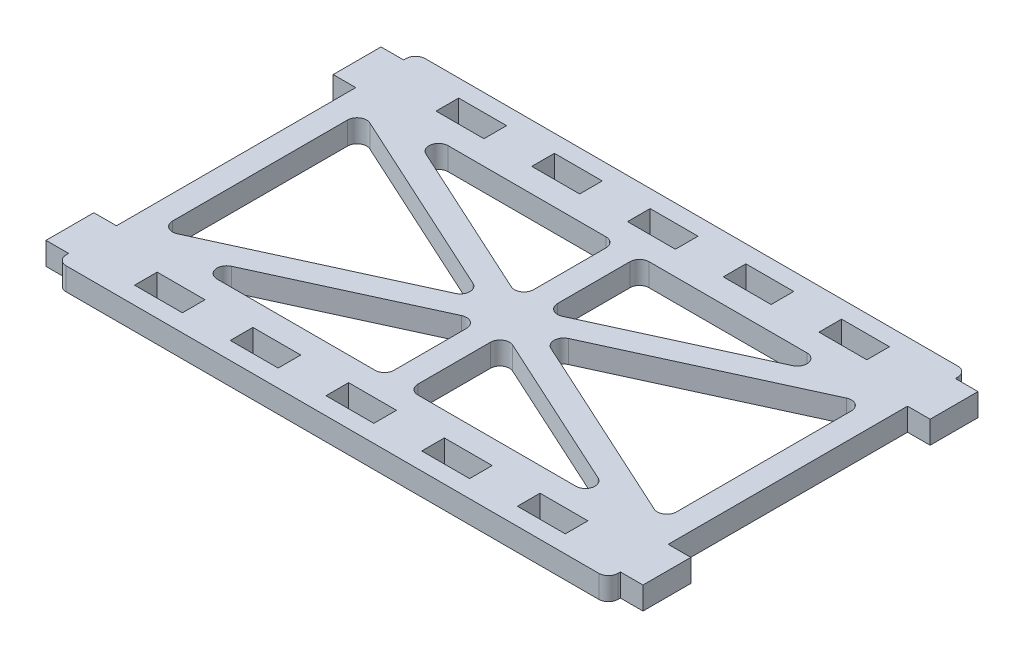
SolidWorks part; units mm, degrees
ref_plane "Front Plane" through (0, 0, 0) normal (0, 0, 1) x (1, 0, 0)
ref_plane "Top Plane" through (0, 0, 0) normal (0, 1, 0) x (1, 0, 0)
ref_plane "Right Plane" through (0, 0, 0) normal (1, 0, 0) x (0, 0, -1)
sketch "Sketch1" plane through (0, 0, 0) normal (0, 1, 0) x (1, 0, 0)
  line L1 (76.2, -50.8) -> (-76.2, -50.8) construction
  line L2 (76.2, -50.8) -> (76.2, 50.8) construction
  line L3 (76.2, 50.8) -> (-76.2, 50.8) construction
  line L4 (-76.2, -50.8) -> (-76.2, 50.8) construction
  line L5 (76.2, -50.8) -> (-76.2, 50.8) construction
  line L6 (76.2, 50.8) -> (-76.2, -50.8) construction
  line L7 (73.2, -47.625) -> (-73.2, -47.625)
  line L8 (73.2, -47.625) -> (73.2, 47.625)
  line L9 (73.2, 47.625) -> (-73.2, 47.625)
  line L10 (-73.2, -47.625) -> (-73.2, 47.625)
  line L11 (73.2, -47.625) -> (-73.2, 47.625) construction
  line L12 (73.2, 47.625) -> (-73.2, -47.625) construction
  line L13 (-73.2, -50.8) -> (-79.2, -50.8) construction
  line L14 (-73.2, -50.8) -> (-73.2, 50.8) construction
  line L15 (-73.2, 50.8) -> (-79.2, 50.8) construction
  line L16 (-79.2, -50.8) -> (-79.2, 50.8) construction
  line L17 (-73.2, -50.8) -> (-79.2, 50.8) construction
  line L18 (-73.2, 50.8) -> (-79.2, -50.8) construction
  line L19 (73.2, -50.8) -> (79.2, -50.8) construction
  line L20 (73.2, -50.8) -> (73.2, 50.8) construction
  line L21 (73.2, 50.8) -> (79.2, 50.8) construction
  line L22 (79.2, -50.8) -> (79.2, 50.8) construction
  line L23 (73.2, -50.8) -> (79.2, 50.8) construction
  line L24 (73.2, 50.8) -> (79.2, -50.8) construction
  point P0 (0, 0)
  point P6 (0, 0)
  point P11 (-76.2, 0)
  point P16 (76.2, 0)
  dimension "D1" = 152.4
  dimension "D2" = 101.6
  dimension "D4" = 6
  dimension "D5" = 95.25
extrude "Boss-Extrude1" add sketch "Sketch1" along normal mid plane 6
sketch "Sketch2" plane through (0, 3, 0) normal (0, 1, 0) x (1, 0, 0)
  line L0 (-73.2, 47.625) -> (-73.2, -47.625) construction
  line L1 (-79.2, 44.45) -> (-73.2, 44.45)
  line L2 (-79.2, 44.45) -> (-79.2, 31.75)
  line L3 (-79.2, 31.75) -> (-73.2, 31.75)
  line L4 (-73.2, 44.45) -> (-73.2, 31.75)
  line L5 (-79.2, 44.45) -> (-73.2, 31.75) construction
  line L6 (-79.2, 31.75) -> (-73.2, 44.45) construction
  line L7 (-79.2, -31.75) -> (-73.2, -31.75)
  line L8 (-79.2, -31.75) -> (-79.2, -44.45)
  line L9 (-79.2, -44.45) -> (-73.2, -44.45)
  line L10 (-73.2, -31.75) -> (-73.2, -44.45)
  line L11 (-79.2, -31.75) -> (-73.2, -44.45) construction
  line L12 (-79.2, -44.45) -> (-73.2, -31.75) construction
  line L13 (-76.2, 38.1) -> (-76.2, -38.1) construction
  line L14 (-76.2, 0) -> (0, 0) construction
  point P0 (-76.2, 38.1)
  point P5 (-76.2, -38.1)
  dimension "D1" = 12.7
  dimension "D2" = 6
  dimension "D3" = 76.2
extrude "Boss-Extrude2" add sketch "Sketch2" against normal up to surface (6 mm away) up to face at (0, -3, 0)
mirror "Mirror1" about plane through (0, 0, 0) normal (1, 0, 0) of "Boss-Extrude2"
sketch "Sketch3" plane through (0, 3, 0) normal (0, 1, 0) x (1, 0, 0)
  line L0 (0, 0) -> (0, 22.4302) construction
  line L5 (0, 0) -> (32.0176, 0) construction
  line L6 (73.2, -47.625) -> (-73.2, -47.625) construction
  line B0 (-6.35, -37.005) -> (-6.35, -43.005)
  line B1 (-6.35, -37.005) -> (6.35, -37.005)
  line B2 (6.35, -37.005) -> (6.35, -43.005)
  line B3 (-6.35, -43.005) -> (6.35, -43.005)
  line B4 (-6.35, -37.005) -> (6.35, -43.005) construction
  line B5 (6.35, -37.005) -> (-6.35, -43.005) construction
  line B6 (-6.35, 43.005) -> (-6.35, 37.005)
  line B7 (-6.35, 43.005) -> (6.35, 43.005)
  line B8 (6.35, 43.005) -> (6.35, 37.005)
  line B9 (-6.35, 37.005) -> (6.35, 37.005)
  dimension "D1" = 7.62
sketch_block_instance "SlotGeometry-1"
sketch_block "SlotGeometry" parameters "D1"=13.9309, "D2"=5.1577
sketch_block_instance "SlotGeometry-2"
extrude "Cut-Extrude1" cut sketch "Sketch3" against normal through all both and the other way through all
pattern_linear "LPattern3" count 3 spacing 25.4 along (1, 0, 0) count 3 spacing 25.4 along (-1, 0, 0) of "Cut-Extrude1"
sketch "Sketch4" plane through (0, 3, 0) normal (0, 1, 0) x (1, 0, 0)
  line L0 (-73.2, 31.75) -> (-73.2, -31.75) construction
  line L1 (-73.2, 37.005) -> (73.2, 37.005) construction
  line L2 (-73.2, 37.005) -> (-73.2, -37.005) construction
  line L3 (-73.2, -37.005) -> (73.2, -37.005) construction
  line L4 (73.2, 37.005) -> (73.2, -37.005) construction
  line L5 (73.2, -31.75) -> (73.2, 31.75) construction
  line L6 (-31.75, 37.005) -> (-19.05, 37.005) construction
  line L7 (-44.45, -37.005) -> (-57.15, -37.005) construction
  line L8 (-66.85, 30.655) -> (66.85, -30.655) construction
  line L9 (66.85, 30.655) -> (-66.85, -30.655) construction
  line L10 (0, 37.005) -> (0, -37.005) construction
  line L11 (-66.85, 30.655) -> (66.85, 30.655)
  line L12 (66.85, 30.655) -> (66.85, -30.655)
  line L13 (-66.85, -30.655) -> (66.85, -30.655)
  line L14 (-66.85, 30.655) -> (-66.85, -30.655)
  line L15 (-68.1734, 27.769) -> (65.5266, -33.541)
  line L16 (65.5266, 33.541) -> (-68.1734, -27.769)
  line L17 (-3.175, 37.005) -> (-3.175, -37.005)
  line L18 (-65.5266, 33.541) -> (68.1734, -27.769)
  line L19 (68.1734, 27.769) -> (-65.5266, -33.541)
  line L20 (3.175, 37.005) -> (3.175, -37.005)
  dimension "D1" = 6.35
  dimension "D2" = 3.175
  dimension "D3" = 3.175
extrude "Cut-Extrude2" cut sketch "Sketch4" against normal through all contours L11 L18 L17 | L16 L15 L14 | L17 L19 L13 | L15 L20 L13 | L12 L19 L18 | L11 L20 L16
fillet "Fillet1" radius 2.54 22 edges at (-3.175, 0, 30.655) (-59.2329, 0, 30.655) (-3.175, 0, 4.9488) (-66.85, 0, 27.1621) (-66.85, 0, -27.1621) (-7.6171, 0, 0) (-3.175, 0, -30.655) (-59.2329, 0, -30.655) (-3.175, 0, -4.9488) (59.2329, 0, -30.655) (3.175, 0, -30.655) (3.175, 0, -4.9488) (66.85, 0, 27.1621) (66.85, 0, -27.1621) (7.6171, 0, 0) (59.2329, 0, 30.655) (3.175, 0, 30.655) (3.175, 0, 4.9488) (73.2, 0, -47.625) (73.2, 0, 47.625) (-73.2, 0, 47.625) (-73.2, 0, -47.625)
